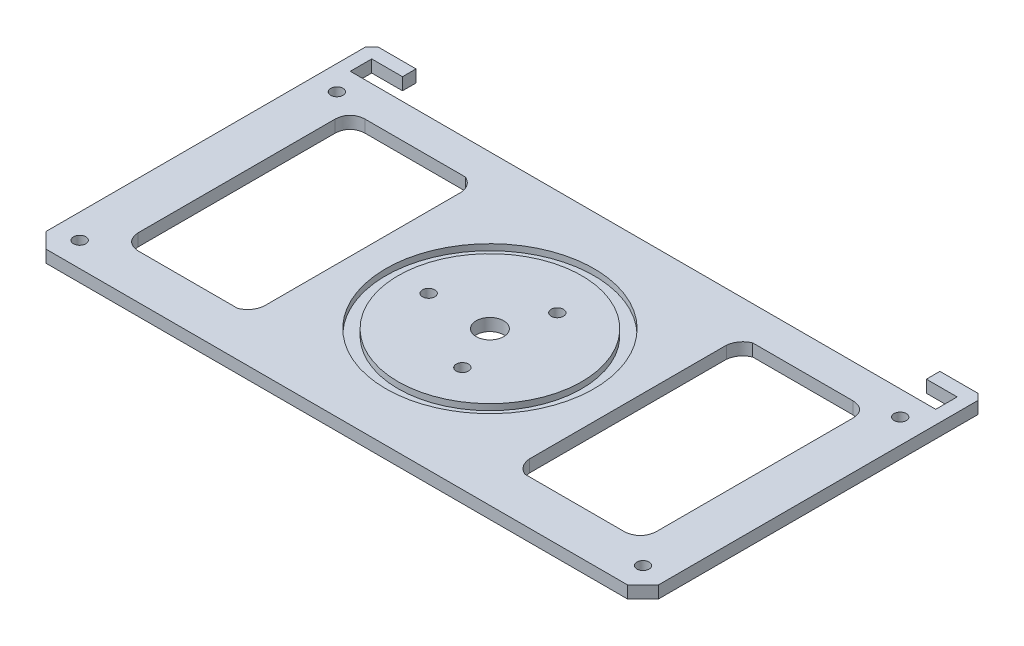
SolidWorks part; units mm, degrees
ref_plane "Plan de face" through (0, 0, 0) normal (0, 0, 1) x (1, 0, 0)
ref_plane "Plan de dessus" through (0, 0, 0) normal (0, 1, 0) x (1, 0, 0)
ref_plane "Plan de droite" through (0, 0, 0) normal (1, 0, 0) x (0, 0, -1)
sketch "Esquisse2" plane through (0, 0, 0) normal (0, 1, 0) x (1, 0, 0)
  line L0 (-100, 50) -> (-100, -50)
  line L1 (-55, 0) -> (55, 0) construction
  line L2 (-100, 50) -> (100, 50)
  line L3 (0, -55) -> (0, 55) construction
  line L4 (100, 50) -> (100, -50)
  line L5 (-100, -50) -> (100, -50)
  circle A0 centre (0, 0) radius 4.5
  circle A1 centre (6.5, 15.5) radius 2
  circle A2 centre (6.5, -15.5) radius 2
  circle A3 centre (-20, 0) radius 2
  circle A4 centre (92, 42) radius 2
  circle A5 centre (-92, 42) radius 2
  circle A6 centre (-92, -42) radius 2
  circle A7 centre (92, -42) radius 2
  point P5 (-100, 0)
  point P9 (0, 50)
  point P10 (100, 0)
  point P11 (0, -50)
  dimension "D3" = 9
  dimension "D5" = 4
  dimension "D7" = 4
  dimension "D9" = 4
  dimension "D1" = 100
  dimension "D2" = 200
  dimension "D4" = 15.5
  dimension "D6" = 6.5
  dimension "D8" = 20
  dimension "D10" = 8
  dimension "D11" = 8
extrude "Boss.-Extru.1" add sketch "Esquisse2" along normal blind 4
sketch "Esquisse3" plane through (0, 4, 0) normal (0, 1, 0) x (1, 0, 0)
  line L0 (-82.4227, 31.378) -> (-82.4227, -31.3394)
  line L1 (-75.998, 36.9993) -> (-27.5067, 36.9993)
  line L2 (-75.998, -36.9993) -> (-27.5067, -36.9993)
  line L3 (-2.2, 0) -> (2.2, 0) construction
  line L4 (0, -2.2) -> (0, 2.2) construction
  line L5 (75.998, -36.9993) -> (27.5067, -36.9993)
  line L6 (75.998, 36.9993) -> (27.5067, 36.9993)
  line L7 (82.4227, 31.378) -> (82.4227, -31.3394)
  circle A0 centre (0, 0) radius 30
  circle A1 centre (0, 0) radius 34
  spline S0 degree 3 poles (-27.5067, 36.9993) (-23.7279, 35.2247) (-25.9325, 29.6926) (-32.0751, 25.6542) (-36.6033, 19.3219) (-40.2785, 10.7522) (-41.7804, 3.9806) (-41.6858, 0) knots 0 0 0 0 0.189513 0.34705 0.518614 0.723246 1 1 1 1
  spline S1 degree 2 poles (-75.998, 36.9993) (-80.5164, 35.5432) (-82.4227, 31.378) knots 0 0 0 1 1 1
  spline S2 degree 3 poles (-27.5067, -36.9993) (-23.7279, -35.2247) (-25.9325, -29.6926) (-32.0751, -25.6542) (-36.6033, -19.3219) (-40.2785, -10.7522) (-41.7804, -3.9806) (-41.6858, 0) knots 0 0 0 0 0.189513 0.34705 0.518614 0.723246 1 1 1 1
  spline S3 degree 2 poles (-75.998, -36.9993) (-80.5164, -35.5432) (-82.4227, -31.378) knots 0 0 0 1 1 1
  spline S4 degree 2 poles (75.998, -36.9993) (80.5164, -35.5432) (82.4227, -31.378) knots 0 0 0 1 1 1
  spline S5 degree 3 poles (27.5067, -36.9993) (23.7279, -35.2247) (25.9325, -29.6926) (32.0751, -25.6542) (36.6033, -19.3219) (40.2785, -10.7522) (41.7804, -3.9806) (41.6858, 0) knots 0 0 0 0 0.189513 0.34705 0.518614 0.723246 1 1 1 1
  spline S6 degree 2 poles (75.998, 36.9993) (80.5164, 35.5432) (82.4227, 31.378) knots 0 0 0 1 1 1
  spline S7 degree 3 poles (27.5067, 36.9993) (23.7279, 35.2247) (25.9325, 29.6926) (32.0751, 25.6542) (36.6033, 19.3219) (40.2785, 10.7522) (41.7804, 3.9806) (41.6858, 0) knots 0 0 0 0 0.189513 0.34705 0.518614 0.723246 1 1 1 1
  dimension "D1" = 60
  dimension "D2" = 68
extrude "Enlèv. mat.-Extru.1" cut sketch "Esquisse3" against normal blind 2 contours A1 A0
sketch "Esquisse4" plane through (0, 4, 0) normal (0, 1, 0) x (1, 0, 0)
  line L0 (-84.5783, 34.0189) -> (-84.5783, -30.4283)
  line L1 (-79.7028, 38.8944) -> (-46.946, 38.8944)
  line L2 (-43.2894, 34.0189) -> (-43.2894, -30.4283)
  line L3 (-79.7028, -35.4561) -> (-46.946, -35.4561)
  line L4 (0, -2.2) -> (0, 2.2) construction
  line L5 (79.7028, -35.4561) -> (46.946, -35.4561)
  line L6 (43.2894, 34.0189) -> (43.2894, -30.4283)
  line L7 (79.7028, 38.8944) -> (46.946, 38.8944)
  line L8 (84.5783, 34.0189) -> (84.5783, -30.4283)
  spline S0 degree 2 poles (-79.7028, 38.8944) (-84.2822, 38.5921) (-84.5783, 34.0189) knots 0 0 0 1 1 1
  spline S1 degree 2 poles (-46.946, 38.8944) (-43.8228, 37.558) (-43.2894, 34.0189) knots 0 0 0 1 1 1
  spline S2 degree 2 poles (-84.5783, -30.4283) (-84.142, -34.8339) (-79.7028, -35.4561) knots 0 0 0 1 1 1
  spline S3 degree 2 poles (-43.2894, -30.4283) (-43.6976, -34.0668) (-46.946, -35.4561) knots 0 0 0 1 1 1
  spline S4 degree 2 poles (43.2894, -30.4283) (43.6976, -34.0668) (46.946, -35.4561) knots 0 0 0 1 1 1
  spline S5 degree 2 poles (84.5783, -30.4283) (84.142, -34.8339) (79.7028, -35.4561) knots 0 0 0 1 1 1
  spline S6 degree 2 poles (46.946, 38.8944) (43.8228, 37.558) (43.2894, 34.0189) knots 0 0 0 1 1 1
  spline S7 degree 2 poles (79.7028, 38.8944) (84.2822, 38.5921) (84.5783, 34.0189) knots 0 0 0 1 1 1
extrude "Enlèv. mat.-Extru.2" cut sketch "Esquisse4" against normal blind 10
sketch "Esquisse5" plane through (0, 0, 0) normal (0, -1, 0) x (1, 0, 0)
  line L0 (100, -50) -> (100, -61.4184)
  line L1 (100, -61.4184) -> (85.5569, -61.4184)
  line L2 (85.5569, -61.4184) -> (85.5569, -57)
  line L3 (85.5569, -57) -> (95.6125, -57)
  line L4 (95.6125, -57) -> (95.6125, -50)
  line L5 (100, -50) -> (-100, -50) construction
  line L10 (-100, -50) -> (100, -50)
  line L11 (-100, 50) -> (-100, -50)
  line L12 (100, 50) -> (-100, 50)
  line L13 (100, -50) -> (100, 50)
  line L14 (95.6125, -50) -> (100, -50)
  dimension "D1" = 7
  dimension "D3" = 11.4184
  dimension "D2" = 0
extrude "Boss.-Extru.2" add sketch "Esquisse5" against normal blind 4
mirror "Symétrie1" about plane through (0, 0, 0) normal (1, 0, 0) of "Boss.-Extru.2"
chamfer "Chanfrein1" distance 5 angle 45 2 edges at (-100, 2, 50) (100, 2, 50)
chamfer "Chanfrein2" distance 2 angle 45 2 edges at (100, 2, -61.4184) (-100, 2, -61.4184)
